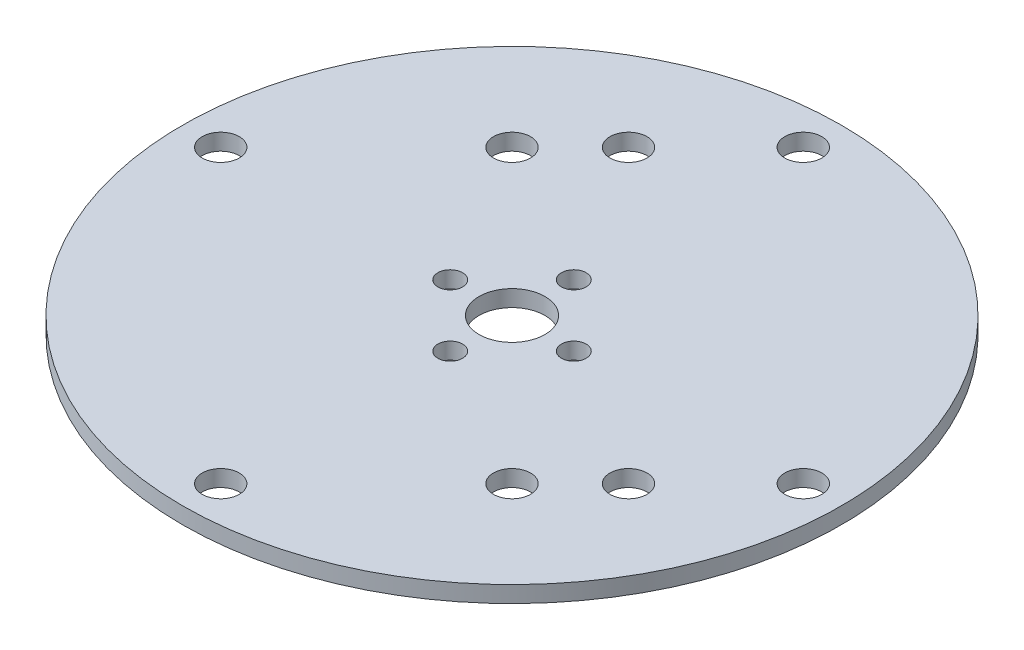
SolidWorks part; units mm, degrees
material "1060 Alloy"
ref_plane "Front Plane" through (0, 0, 0) normal (0, 0, 1) x (1, 0, 0)
ref_plane "Top Plane" through (0, 0, 0) normal (0, 1, 0) x (1, 0, 0)
ref_plane "Right Plane" through (0, 0, 0) normal (1, 0, 0) x (0, 0, -1)
sketch "Sketch1" plane through (0, 0, 0) normal (0, 1, 0) x (1, 0, 0)
  line L0 (0, 35.3553) -> (-35.3553, 0) construction
  line L1 (-28.2843, 28.2843) -> (28.2843, -28.2843) construction
  line L2 (-35.3553, 0) -> (0, -35.3553) construction
  line L3 (0, -35.3553) -> (35.3553, 0) construction
  line L4 (35.3553, 0) -> (0, 35.3553) construction
  line L5 (0, 35.3553) -> (0, -35.3553) construction
  circle A0 centre (0, 0) radius 40
  circle A1 centre (0, 0) radius 35.3553 construction
  circle A2 centre (0, 35.3553) radius 2.25
  circle A3 centre (35.3553, 0) radius 2.25
  circle A4 centre (0, -35.3553) radius 2.25
  circle A5 centre (-35.3553, 0) radius 2.25
  circle A6 centre (-17.6777, 17.6777) radius 2.25
  circle A7 centre (17.6777, -17.6777) radius 2.25
  circle A8 centre (-10.6066, 24.7487) radius 2.25
  circle A9 centre (24.7487, -10.6066) radius 2.25
  circle A10 centre (0, 0) radius 4
  circle A11 centre (0, 0) radius 7.5 construction
  circle A12 centre (0, 7.5) radius 1.5
  circle A13 centre (7.5, 0) radius 1.5
  circle A14 centre (0, -7.5) radius 1.5
  circle A15 centre (-7.5, 0) radius 1.5
  point P15 (0, 0)
  point P36 (0, 0)
  dimension "D1" = 80
  dimension "D2" = 50
  dimension "D3" = 4.5
  dimension "D5" = 4.5
  dimension "D6" = 4.5
  dimension "D7" = 4.5
  dimension "D8" = 10
  dimension "D9" = 4.5
  dimension "D10" = 10
  dimension "D12" = 8
  dimension "D13" = 15
  dimension "D14" = 3
  dimension "D11" = 45
  dimension "D16" = 50
  dimension "D17" = 50
  dimension "D4" = 4
  dimension "D15" = 4
extrude "Boss-Extrude2" add sketch "Sketch1" along normal blind 2
